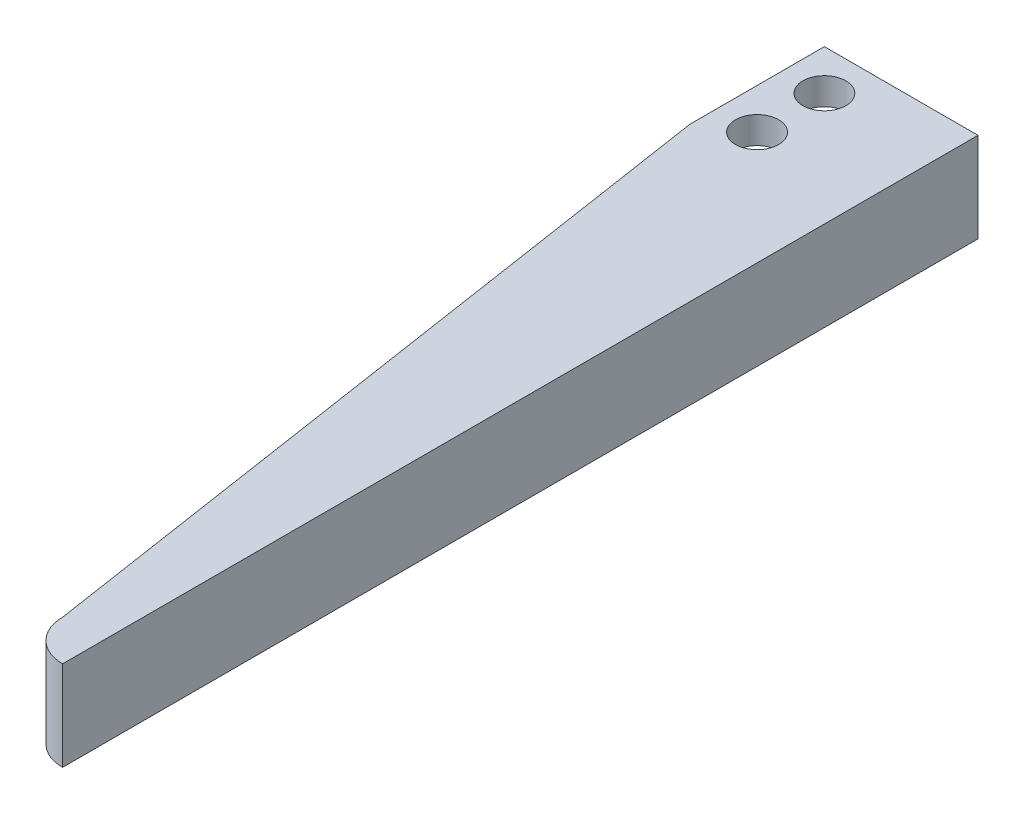
SolidWorks part; units mm, degrees
ref_plane "Front Plane" through (0, 0, 0) normal (0, 0, 1) x (1, 0, 0)
ref_plane "Top Plane" through (0, 0, 0) normal (0, 1, 0) x (1, 0, 0)
ref_plane "Right Plane" through (0, 0, 0) normal (1, 0, 0) x (0, 0, -1)
sketch "Sketch1" plane through (0, 0, 0) normal (0, 1, 0) x (1, 0, 0)
  line L0 (-5.7062, 0) -> (5.7062, 0)
  line L1 (-5.7062, 0) -> (-5.7062, -10)
  line L2 (-5.7062, -10) -> (2.7063, -65)
  line L5 (5.7062, 0) -> (5.7063, -65) construction
  line L6 (5.7063, -68) -> (5.7062, 0)
  arc A0 (2.7063, -65) -> (5.7063, -68) centre (5.7063, -65) ccw
  circle A1 centre (-2.7062, -3) radius 1.6
  circle A2 centre (-2.7062, -8) radius 1.6
  point P3 (0, 0)
  dimension "D1" = 3
  dimension "D8" = 3.2
  dimension "D2" = 11.4125
  dimension "D3" = 10
  dimension "D4" = 55
  dimension "D5" = 3
  dimension "D6" = 5
  dimension "D7" = 3
extrude "Boss-Extrude1" add sketch "Sketch1" along normal blind 2
sketch "Sketch2" plane through (0, 0, 0) normal (0, -1, 0) x (1, 0, 0)
  line L0 (5.7062, 0) -> (-5.7062, 0) construction
  line L1 (5.7063, 68) -> (5.7063, 0)
  line L8 (5.7063, 0) -> (2.7063, 0)
  line L9 (2.7063, 65) -> (2.7063, 0)
  line L10 (5.7063, 68) -> (5.7062, 0) construction
  arc A2 (5.7063, 68) -> (2.7063, 65) centre (5.7063, 65) ccw
extrude "Boss-Extrude2" add sketch "Sketch2" along normal blind 4.6625
ref_plane "Plane1" through (0, -4.6625, 0) normal (0, -1, 0) x (-1, 0, 0)
